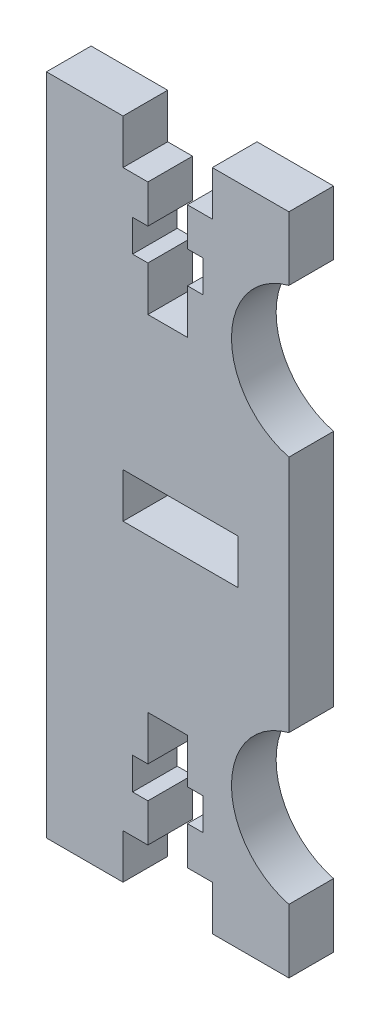
SolidWorks part; units mm, degrees
material "Balsa"
ref_plane "Front Plane" through (0, 0, 0) normal (0, 0, 1) x (1, 0, 0)
ref_plane "Top Plane" through (0, 0, 0) normal (0, 1, 0) x (1, 0, 0)
ref_plane "Right Plane" through (0, 0, 0) normal (1, 0, 0) x (0, 0, -1)
sketch "Sketch1" plane through (0, 0, 0) normal (0, 0, 1) x (1, 0, 0)
  line L0 (3.5, 26) -> (3.5, 22.5)
  line L1 (-9.5, -26) -> (9.5, -26) construction
  line L2 (-9.5, -26) -> (-9.5, 26)
  line L3 (-9.5, 26) -> (9.5, 26) construction
  line L4 (9.5, -26) -> (9.5, 26) construction
  line L5 (0, 26) -> (0, -26) construction
  line L6 (-9.5, 0) -> (9.5, 0) construction
  line L7 (3.5, 22.5) -> (1.55, 22.5)
  line L8 (1.55, 22.5) -> (1.55, 19.5)
  line L9 (1.55, 19.5) -> (2.75, 19.5)
  line L10 (2.75, 19.5) -> (2.75, 17)
  line L11 (2.75, 17) -> (1.55, 17)
  line L12 (1.55, 17) -> (1.55, 13.5)
  line L13 (1.55, 13.5) -> (-1.55, 13.5)
  line L14 (-1.55, 17) -> (-1.55, 13.5)
  line L15 (-2.75, 17) -> (-1.55, 17)
  line L16 (-2.75, 19.5) -> (-2.75, 17)
  line L17 (-1.55, 19.5) -> (-2.75, 19.5)
  line L18 (-1.55, 22.5) -> (-1.55, 19.5)
  line L19 (-3.5, 22.5) -> (-1.55, 22.5)
  line L20 (-3.5, 26) -> (-3.5, 22.5)
  line L21 (9.5, 26) -> (3.5, 26)
  line L22 (-3.5, 26) -> (-9.5, 26)
  line L23 (3.5, -26) -> (3.5, -22.5)
  line L24 (3.5, -22.5) -> (1.55, -22.5)
  line L25 (1.55, -22.5) -> (1.55, -19.5)
  line L26 (1.55, -19.5) -> (2.75, -19.5)
  line L27 (2.75, -19.5) -> (2.75, -17)
  line L28 (2.75, -17) -> (1.55, -17)
  line L29 (1.55, -17) -> (1.55, -13.5)
  line L30 (1.55, -13.5) -> (-1.55, -13.5)
  line L31 (-1.55, -17) -> (-1.55, -13.5)
  line L32 (-2.75, -17) -> (-1.55, -17)
  line L33 (-2.75, -19.5) -> (-2.75, -17)
  line L34 (-1.55, -19.5) -> (-2.75, -19.5)
  line L35 (-1.55, -22.5) -> (-1.55, -19.5)
  line L36 (-3.5, -22.5) -> (-1.55, -22.5)
  line L37 (-3.5, -26) -> (-3.5, -22.5)
  line L38 (9.5, -26) -> (3.5, -26)
  line L39 (-3.5, -26) -> (-9.5, -26)
  line L40 (9.5, 26) -> (9.5, 21)
  line L41 (9.5, 9.3501) -> (9.5, -9.3501)
  line L42 (9.5, -21) -> (9.5, -26)
  line L43 (0, -2.8962) -> (0, 2.8316) construction
  arc A2 (9.5, -21) -> (9.5, -9.3501) centre (11.02, -15.1751) cw
  arc A3 (9.5, 21) -> (9.5, 9.3501) centre (11.02, 15.1751) ccw
  point P0 (0, 0)
  point P14 (0, 13.5)
  point P40 (5, -15.1751)
  dimension "D11" = 4.5
  dimension "D10" = 6.02
  dimension "D1" = 19
  dimension "D2" = 52
  dimension "D3" = 7
  dimension "D4" = 3.5
  dimension "D5" = 3.1
  dimension "D6" = 3
  dimension "D7" = 2.5
  dimension "D8" = 5.5
  dimension "D9" = 3.5
  dimension "D12" = 0
  dimension "D13" = 5
extrude "Boss-Extrude1" add sketch "Sketch1" along normal blind 3.5
sketch "Sketch2" plane through (0, 0, 3.5) normal (0, 0, 1) x (1, 0, 0)
  line L1 (5.5, -1.5) -> (-3.5, -1.5)
  line L2 (5.5, -1.5) -> (5.5, 2)
  line L3 (5.5, 2) -> (-3.5, 2)
  line L4 (-3.5, -1.5) -> (-3.5, 2)
  line L5 (-3.5, -22.5) -> (-1.55, -22.5) construction
  line L6 (-9.5, 26) -> (-9.5, -26) construction
  dimension "D1" = 9
  dimension "D2" = 3.5
  dimension "D3" = 21
  dimension "D4" = 6
extrude "Cut-Extrude1" cut sketch "Sketch2" against normal through all
